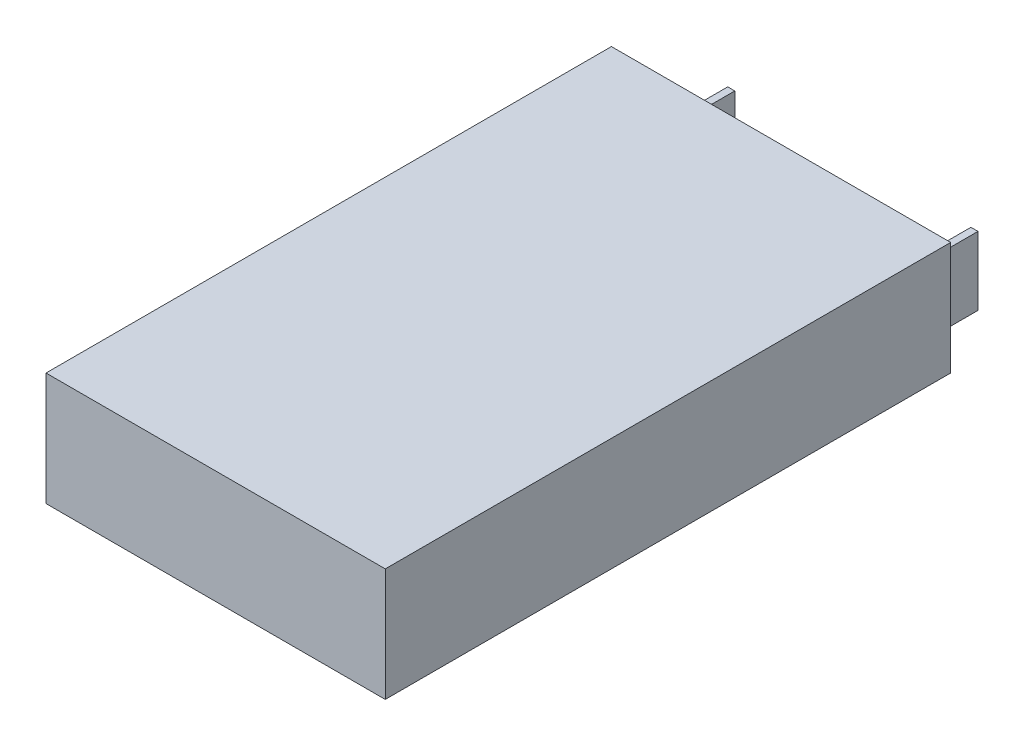
SolidWorks part; units mm, degrees
ref_plane "Front Plane" through (0, 0, 0) normal (0, 0, 1) x (1, 0, 0)
ref_plane "Top Plane" through (0, 0, 0) normal (0, 1, 0) x (1, 0, 0)
ref_plane "Right Plane" through (0, 0, 0) normal (1, 0, 0) x (0, 0, -1)
sketch "Sketch1" plane through (0, 0, 0) normal (0, 1, 0) x (1, 0, 0)
  line L0 (28.9941, 63.5) -> (-28.9941, 63.5)
  line L1 (38.1, 63.5) -> (-38.1, 63.5)
  line L2 (38.1, 63.5) -> (38.1, -63.5)
  line L3 (38.1, -63.5) -> (-38.1, -63.5)
  line L4 (-38.1, 63.5) -> (-38.1, -63.5)
  line L5 (38.1, 63.5) -> (-38.1, -63.5) construction
  line L6 (38.1, -63.5) -> (-38.1, 63.5) construction
  point P0 (0, 0)
  point P9 (0, 63.5)
  dimension "D1" = 127
  dimension "D2" = 76.2
  dimension "D3" = 57.9882
extrude "Boss-Extrude1" add sketch "Sketch1" along normal blind 25.4 contours L1 L4 L3 L2 L0
sketch "Sketch2" plane through (0, 25.4, 0) normal (0, 1, 0) x (1, 0, 0)
  line L0 (28.9941, 63.5) -> (-28.9941, 63.5)
  line L1 (38.1, 63.5) -> (-38.1, 63.5) construction
  point P5 (0, 63.5)
  dimension "D1" = 57.9882
sketch "Sketch5" plane through (0, 0, -63.5) normal (0, 0, -1) x (-1, 0, 0)
  line L0 (-28.9941, 0) -> (-28.9941, 15.3772)
  line L1 (-38.1, 0) -> (38.1, 0) construction
  line L2 (27.2206, 0) -> (27.2206, 15.3772)
  line L4 (-28.9941, 15.3772) -> (-27.4066, 15.3772)
  line L5 (-28.9941, 15.3772) -> (-28.9941, 0)
  line L6 (-28.9941, 0) -> (-27.4066, 0)
  line L7 (-27.4066, 15.3772) -> (-27.4066, 0)
  line L8 (27.2206, 15.3772) -> (25.6331, 15.3772)
  line L9 (27.2206, 15.3772) -> (27.2206, 0)
  line L10 (27.2206, 0) -> (25.6331, 0)
  line L11 (25.6331, 15.3772) -> (25.6331, 0)
  line M11 (-38.1, 0) -> (38.1, 0)
  dimension "D1" = 1.5875
  dimension "D2" = 1.5875
  dimension "D3" = 15.3772
  dimension "D4" = 15.3772
extrude "Boss-Extrude3" add sketch "Sketch5" along normal blind 15.24 contours L7 L4 L0 M11 | L8 L11 L2 M11
